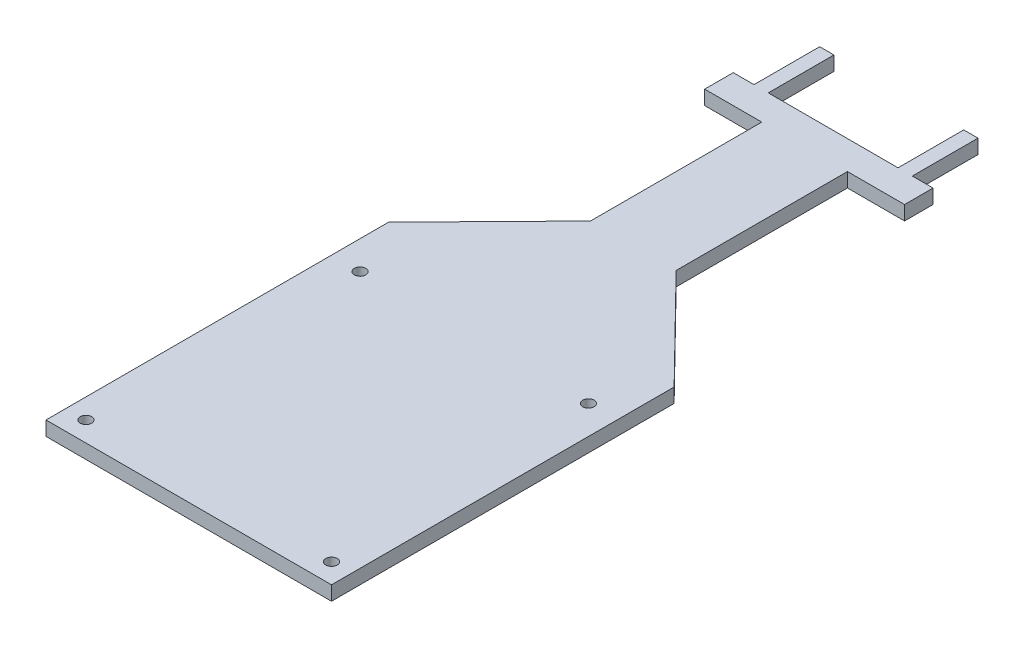
SolidWorks part; units mm, degrees
ref_plane "Front Plane" through (0, 0, 0) normal (0, 0, 1) x (1, 0, 0)
ref_plane "Top Plane" through (0, 0, 0) normal (0, 1, 0) x (1, 0, 0)
ref_plane "Right Plane" through (0, 0, 0) normal (1, 0, 0) x (0, 0, -1)
sketch "Sketch1" plane through (0, 0, 0) normal (0, 1, 0) x (1, 0, 0)
  line L0 (0, 0) -> (0, 155.7071) construction
  line L2 (-50, 60) -> (-50, -60)
  line L3 (-50, -60) -> (50, -60)
  line L4 (50, 60) -> (50, -60)
  line L5 (-50, 60) -> (50, -60) construction
  line L6 (-50, -60) -> (50, 60) construction
  line L7 (-50, 60) -> (-15, 95.7071)
  line L8 (-15, 155.7071) -> (-15, 95.7071)
  line L10 (15, 155.7071) -> (15, 95.7071)
  line L11 (50, 60) -> (15, 95.7071)
  line L12 (-27.729, 165.7071) -> (-27.729, 188.7071)
  line L13 (-35, 155.7071) -> (-15, 155.7071)
  line L14 (-35, 155.7071) -> (-35, 165.7071)
  line L15 (-35, 165.7071) -> (-27.729, 165.7071)
  line L16 (35, 155.7071) -> (35, 165.7071)
  line L17 (35, 155.7071) -> (15, 155.7071)
  line L18 (-27.729, 188.7071) -> (-22.729, 188.7071)
  line L19 (-22.729, 188.7071) -> (-22.729, 165.7071)
  line L20 (-22.729, 165.7071) -> (22.729, 165.7071)
  line L21 (22.729, 188.7071) -> (22.729, 165.7071)
  line L22 (27.729, 188.7071) -> (22.729, 188.7071)
  line L23 (27.729, 165.7071) -> (27.729, 188.7071)
  line L24 (27.729, 165.7071) -> (35, 165.7071)
  line L25 (-50, 60) -> (50, 60) construction
  circle A0 centre (40, 40) radius 2
  circle A1 centre (-40, 40) radius 2
  circle A2 centre (-43, -53) radius 2
  circle A3 centre (43, -53) radius 2
  point P0 (0, 0)
  point P17 (0, 165.7071)
  dimension "D10" = 10
  dimension "D12" = 4
  dimension "D14" = 7
  dimension "D1" = 120
  dimension "D2" = 100
  dimension "D3" = 30
  dimension "D4" = 70
  dimension "D5" = 60
  dimension "D6" = 50
  dimension "D7" = 10
  dimension "D8" = 5
  dimension "D9" = 23
  dimension "D11" = 20
  dimension "D13" = 10
  dimension "D15" = 7
extrude "Boss-Extrude1" add sketch "Sketch1" along normal blind 5
